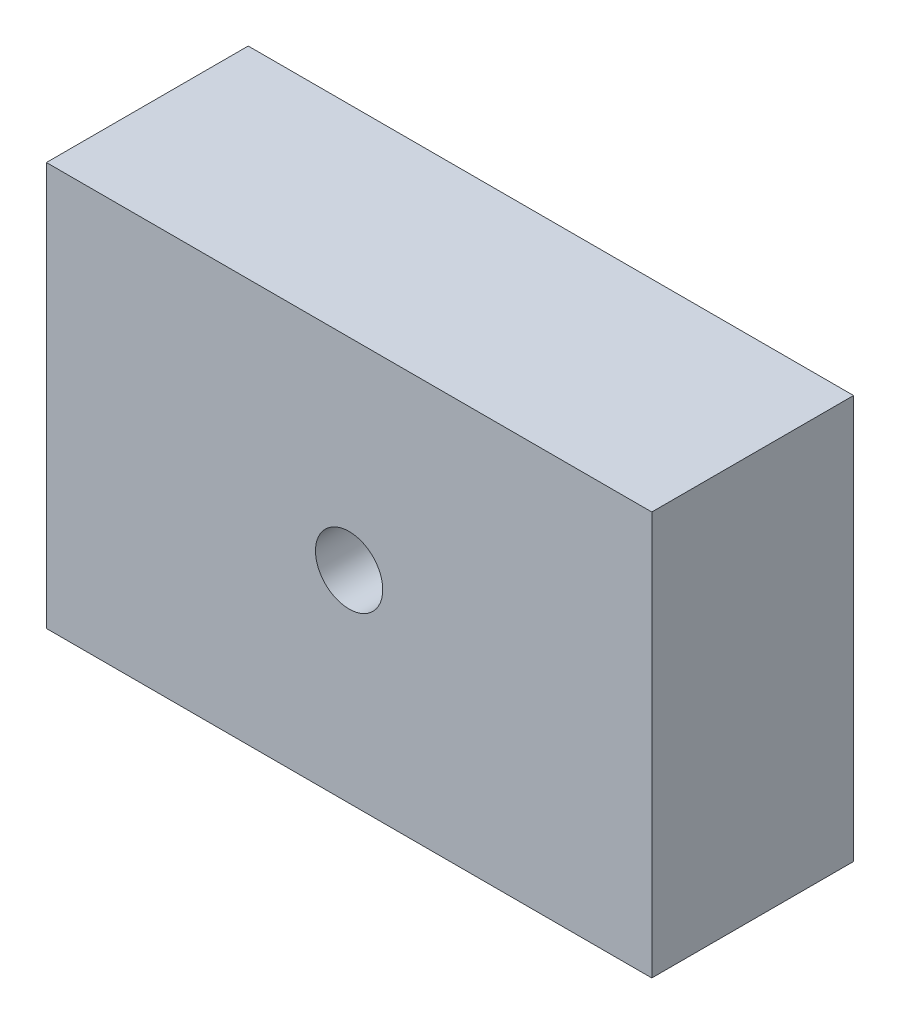
SolidWorks part; units mm, degrees
ref_plane "Front Plane" through (0, 0, 0) normal (0, 0, 1) x (1, 0, 0)
ref_plane "Top Plane" through (0, 0, 0) normal (0, 1, 0) x (1, 0, 0)
ref_plane "Right Plane" through (0, 0, 0) normal (1, 0, 0) x (0, 0, -1)
sketch "Sketch1" plane through (0, 0, 0) normal (0, 0, 1) x (1, 0, 0)
  line L1 (0, 0) -> (90, 0)
  line L2 (0, 0) -> (0, 60)
  line L3 (0, 60) -> (90, 60)
  line L4 (90, 0) -> (90, 60)
  dimension "D1" = 60
  dimension "D2" = 90
extrude "Boss-Extrude1" add sketch "Sketch1" along normal blind 30
sketch "Sketch2" plane through (0, 0, 30) normal (0, 0, 1) x (1, 0, 0)
  line L0 (0, 60) -> (90, 0) construction
  line L1 (0, 0) -> (90, 60) construction
  circle A0 centre (45, 30) radius 5
  dimension "D1" = 10
extrude "Cut-Extrude1" cut sketch "Sketch2" against normal blind 10 contours A0
